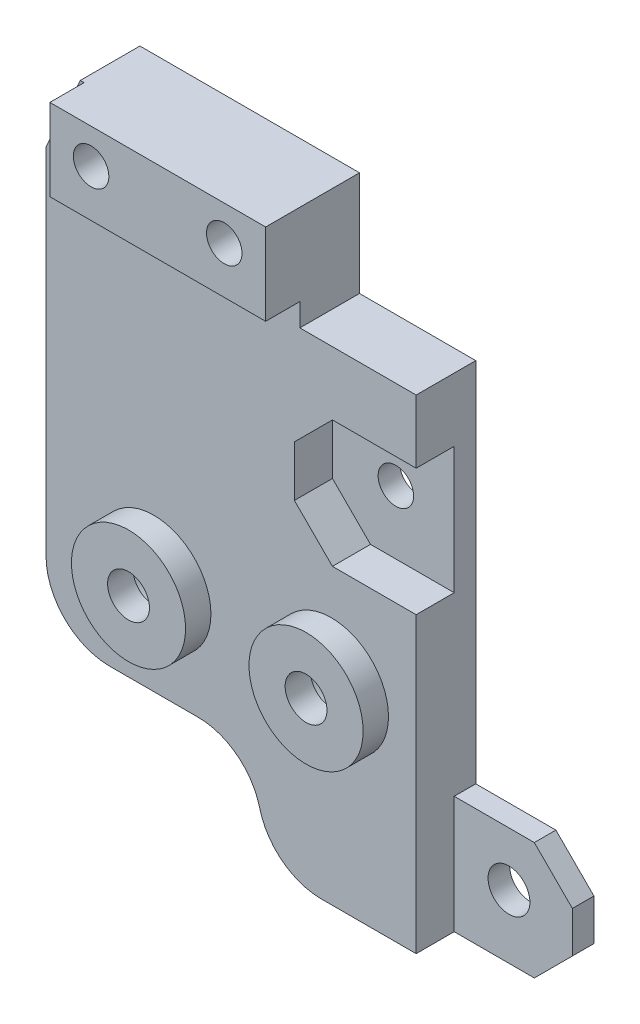
SolidWorks part; units mm, degrees
ref_plane "前视基准面" through (0, 0, 0) normal (0, 0, 1) x (1, 0, 0)
ref_plane "上视基准面" through (0, 0, 0) normal (0, 1, 0) x (1, 0, 0)
ref_plane "右视基准面" through (0, 0, 0) normal (1, 0, 0) x (0, 0, -1)
other "Configuration Table"
sketch "Sketch2" plane through (0, 0, 0) normal (0, 0, 1) x (1, 0, 0)
  line L1 (5.6815, -33.3888) -> (5.6815, -42.6388)
  line L3 (-12.8185, -4.4888) -> (-3.2371, -4.4888) construction
  line L6 (-12.8185, -4.4888) -> (-3.6371, -4.4888)
  line L7 (-32.8185, -4.4888) -> (-32.8185, -41.9888)
  line L8 (-22.8185, -51.9888) -> (21.1815, -51.9888)
  line L9 (31.1815, -41.9888) -> (31.1815, -4.4888)
  line L10 (31.1815, -4.4888) -> (11.1815, -4.4888)
  line L11 (11.1815, -4.4888) -> (11.1815, 0.0112)
  line L12 (-12.8185, 0.0112) -> (-12.8185, -4.4888)
  line L13 (-12.8185, -4.4888) -> (-32.8185, -4.4888)
  line L14 (-32.8185, -4.4888) -> (-32.8185, -35.0888)
  line L20 (-12.8185, -4.4888) -> (-32.8185, -4.4888)
  line L21 (5.6815, -33.3888) -> (-3.6371, -33.3888)
  line L22 (-3.6371, -33.3888) -> (-3.6371, -9.4888)
  line L23 (-3.6371, -4.8888) -> (-3.6371, -9.4888)
  line L24 (31.1815, -33.3888) -> (-3.6371, -33.3888) construction
  line L25 (-3.6371, -4.8888) -> (-3.6371, -4.4888)
  line L26 (-3.2371, -32.9888) -> (-3.2371, -10.6096) construction
  line L27 (-12.8185, -4.8888) -> (-3.6371, -4.8888) construction
  line L28 (31.1815, -32.9888) -> (-3.2371, -32.9888) construction
  line L29 (-3.2371, -32.9888) -> (-3.2371, -9.4888) construction
  line L30 (-3.2371, -4.4888) -> (-3.2371, -9.4888) construction
  line L31 (-20.8185, -35.0888) -> (-32.8185, -35.0888)
  line L32 (-15.8185, -40.0888) -> (-15.8185, -42.6388)
  line L33 (-15.8185, -42.6388) -> (5.6815, -42.6388)
  line L34 (4.4252, -9.4888) -> (-3.2371, -9.4888) construction
  circle A1 centre (-8.2371, -14.4888) radius 1.4
  arc A3 (-32.8185, -41.9888) -> (-22.8185, -51.9888) centre (-22.8185, -41.9888) ccw
  arc A4 (21.1815, -51.9888) -> (31.1815, -41.9888) centre (21.1815, -41.9888) ccw
  arc A5 (11.1815, 0.0112) -> (-12.8185, 0.0112) centre (-0.8185, 0.0112) ccw
  arc A40 (-27.4185, -27.5388) -> (-24.3185, -30.6388) centre (-24.3185, -27.5388) ccw
  arc A41 (-24.3185, -30.6388) -> (-27.4185, -27.5388) centre (-24.3185, -27.5388) ccw
  arc A42 (-27.4185, -27.5388) -> (-24.3185, -30.6388) centre (-24.3185, -27.5388) ccw
  arc A43 (-24.3185, -30.6388) -> (-27.4185, -27.5388) centre (-24.3185, -27.5388) ccw
  circle A45 centre (0.6815, -37.6388) radius 1.65
  arc A46 (-15.8185, -40.0888) -> (-20.8185, -35.0888) centre (-20.8185, -40.0888) ccw
  arc A47 (-13.4185, -27.5388) -> (-10.3185, -30.6388) centre (-10.3185, -27.5388) ccw
  arc A48 (-10.3185, -30.6388) -> (-13.4185, -27.5388) centre (-10.3185, -27.5388) ccw
  arc A49 (-13.4185, -27.5388) -> (-10.3185, -30.6388) centre (-10.3185, -27.5388) ccw
  arc A50 (-10.3185, -30.6388) -> (-13.4185, -27.5388) centre (-10.3185, -27.5388) ccw
  dimension "D5" = 3.3
  dimension "D8" = 10
  dimension "D7" = 2.8
  dimension "D6" = 5
  dimension "D9" = 5
  dimension "D10" = 5
  dimension "D1" = 0
  dimension "D2" = 0.4
  dimension "D3" = 0.4
  dimension "D4" = 0.4
extrude "Boss-Extrude1" add sketch "Sketch2" along normal offset from surface (4.7 mm away) 0.2
sketch "Sketch3" plane through (0, 0, 4.7) normal (0, 0, 1) x (1, 0, 0)
  circle A0 centre (-24.3185, -27.5388) radius 1.65
  circle A1 centre (-10.3185, -27.5388) radius 1.65
  circle A2 centre (-24.3185, -27.5388) radius 4.5
  circle A3 centre (-10.3185, -27.5388) radius 4.5
  dimension "D1" = 9
extrude "Boss-Extrude2" add sketch "Sketch3" along normal blind 2
fillet "Fillet1" radius 5 3 edges at (-15.8185, -42.6388, 2.35) (-32.8185, -35.0888, 2.35) (-32.8185, -4.4888, 2.35)
chamfer "Chamfer1" distance 3 angle 45 2 edges at (5.6815, -33.3888, 2.35) (5.6815, -42.6388, 2.35)
sketch "Sketch4" plane through (0, 0, 4.7) normal (0, 0, 1) x (1, 0, 0)
  line L0 (-11.1233, -42.6388) -> (2.6815, -42.6388) construction
  line L1 (2.6815, -42.6388) -> (5.6815, -39.6388) construction
  line L2 (5.6815, -39.6388) -> (5.6815, -36.3888) construction
  line L3 (5.6815, -36.3888) -> (2.6815, -33.3888) construction
  line L4 (2.6815, -33.3888) -> (-3.6371, -33.3888) construction
  line L5 (-3.6371, -42.6388) -> (2.6815, -42.6388)
  line L6 (2.6815, -42.6388) -> (5.6815, -39.6388)
  line L7 (5.6815, -39.6388) -> (5.6815, -36.3888)
  line L8 (5.6815, -36.3888) -> (2.6815, -33.3888)
  line L9 (2.6815, -33.3888) -> (-3.6371, -33.3888)
  line L10 (-3.6371, -33.3888) -> (-3.6371, -42.6388)
  line L11 (-3.6371, -9.4888) -> (-10.2371, -9.4888)
  line L12 (-3.6371, -33.3888) -> (-3.6371, -4.4888) construction
  line L13 (-13.2371, -12.4888) -> (-13.2371, -16.4888)
  line L14 (-10.2371, -19.4888) -> (-3.6371, -19.4888)
  line L15 (-3.6371, -19.4888) -> (-3.6371, -9.4888)
  line L16 (-10.2371, -9.4888) -> (-13.2371, -12.4888)
  line L17 (-13.2371, -16.4888) -> (-10.2371, -19.4888)
  circle A0 centre (-8.2371, -14.4888) radius 1.4 construction
  point P8 (-13.2371, -9.4888)
  point P12 (-13.2371, -19.4888)
  dimension "D1" = 5
  dimension "D2" = 5
  dimension "D3" = 5
extrude "Cut-Extrude1" cut sketch "Sketch4" against normal blind 3
sketch "Sketch5" plane through (0, 0, 0) normal (0, 0, -1) x (-1, 0, 0)
  line L0 (12.8033, -4.4888) -> (12.8033, 3.7526)
  line L1 (3.6371, -4.4888) -> (27.8185, -4.4888) construction
  line L2 (12.8033, 3.7526) -> (30.1186, 3.7526)
  line L3 (30.1186, 3.7526) -> (32.8185, -2.1196)
  line L4 (32.8185, -2.1196) -> (32.8185, -9.4888)
  line L5 (12.8033, -4.4888) -> (27.8185, -4.4888)
  circle A0 centre (26.5685, 1.0112) radius 1.4
  circle A1 centre (16.0685, 1.0112) radius 1.4
  arc A2 (32.8185, -9.4888) -> (27.8185, -4.4888) centre (27.8185, -9.4888) ccw construction
  arc A3 (32.8185, -9.4888) -> (27.8185, -4.4888) centre (27.8185, -9.4888) ccw
extrude "Boss-Extrude3" add sketch "Sketch5" against normal up to surface (4.7 mm away) up to face at (-15.517, -21.9871, 4.7)
sketch "Sketch6" plane through (0, 0, 4.7) normal (0, 0, 1) x (1, 0, 0)
  line L0 (-30.1186, 3.7526) -> (-12.8033, 3.7526) construction
  line L1 (-29.8185, 3.7526) -> (-12.8033, 3.7526)
  line L2 (-29.8185, 3.7526) -> (-29.8185, -2.6888)
  line L3 (-29.8185, -2.6888) -> (-12.8033, -2.6888)
  line L4 (-12.8033, 3.7526) -> (-12.8033, -2.6888)
  line L5 (-12.8033, 3.7526) -> (-12.8033, -4.4888) construction
  line L6 (-13.2185, -2.4888) -> (-29.4185, -2.4888) construction
  line L7 (-29.8185, -2.0888) -> (-29.8185, 25.1112) construction
  circle A0 centre (-26.5685, 1.0112) radius 1.4
  circle A1 centre (-16.0685, 1.0112) radius 1.4
  dimension "D1" = 0.2
  dimension "D2" = 0
extrude "Boss-Extrude4" add sketch "Sketch6" along normal up to surface (2.7 mm away)
